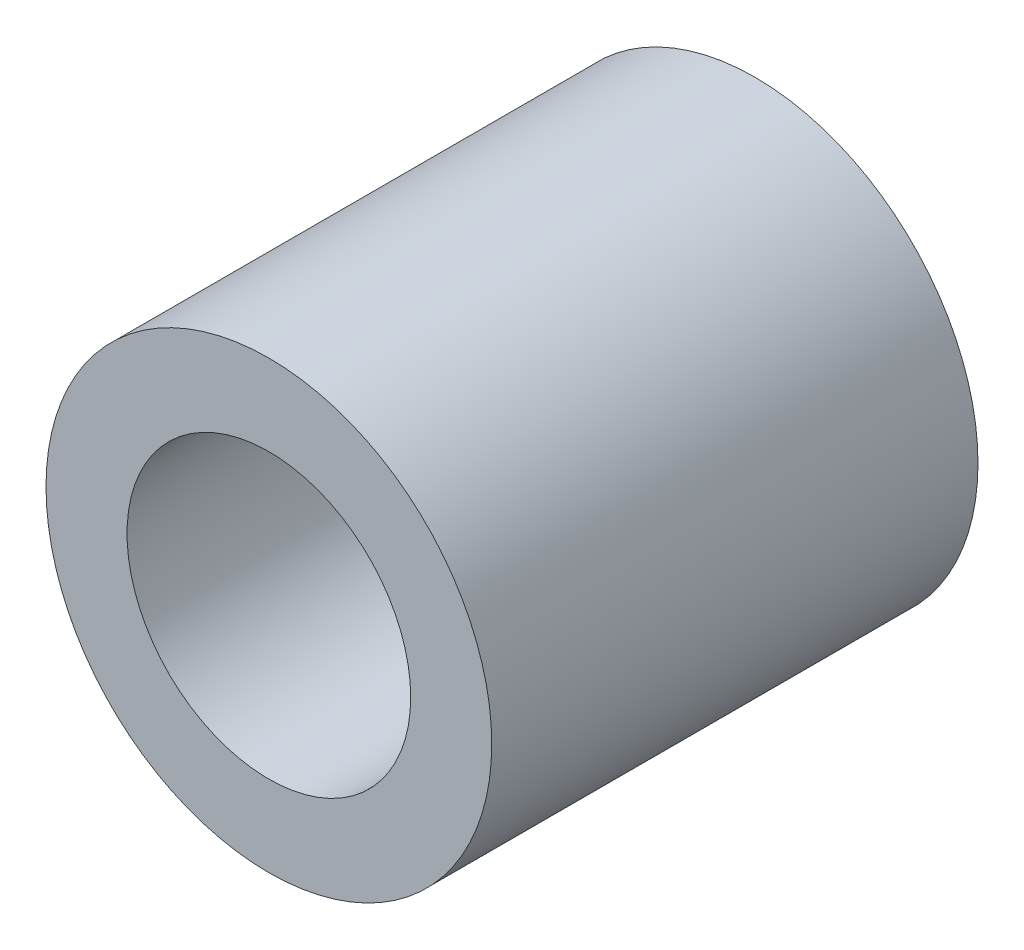
SolidWorks part; units mm, degrees
ref_plane "Ön Düzlem" through (0, 0, 0) normal (0, 0, 1) x (1, 0, 0)
ref_plane "Üst Düzlem" through (0, 0, 0) normal (0, 1, 0) x (1, 0, 0)
ref_plane "Sağ Düzlem" through (0, 0, 0) normal (1, 0, 0) x (0, 0, -1)
sketch "Sketch1" plane through (0, 0, 0) normal (0, 0, 1) x (1, 0, 0)
  circle A0 centre (0, 0) radius 2.5
  circle A1 centre (0, 0) radius 5.5
  dimension "D1" = 5
  dimension "D2" = 3
extrude "Boss-Extrude1" add sketch "Sketch1" along normal blind 20
sketch "Sketch2" plane through (0, 0, 20) normal (0, 0, 1) x (1, 0, 0)
  circle A0 centre (0, 0) radius 2.5
  circle A1 centre (0, 0) radius 2.5 construction
extrude "Boss-Extrude2" add sketch "Sketch2" against normal blind 2 from offset 15 offset against normal yes
sketch "Sketch3" plane through (0, 0, 5) normal (0, 0, 1) x (1, 0, 0)
  circle A0 centre (0, 0) radius 1
  dimension "D1" = 2
extrude "Cut-Extrude1" cut sketch "Sketch3" against normal blind 2
sketch "Sketch4" plane through (0, 0, 20) normal (0, 0, 1) x (1, 0, 0)
  circle A0 centre (0, 0) radius 3.5
  dimension "D1" = 7
extrude "Cut-Extrude3" cut sketch "Sketch4" against normal up to surface (15 mm away) up to face at (1, 0, 5)
sketch "Sketch5" plane through (0, 0, 20) normal (0, 0, 1) x (1, 0, 0)
  circle A0 centre (0, 0) radius 6.684
extrude "Cut-Extrude4" cut sketch "Sketch5" against normal blind 8
